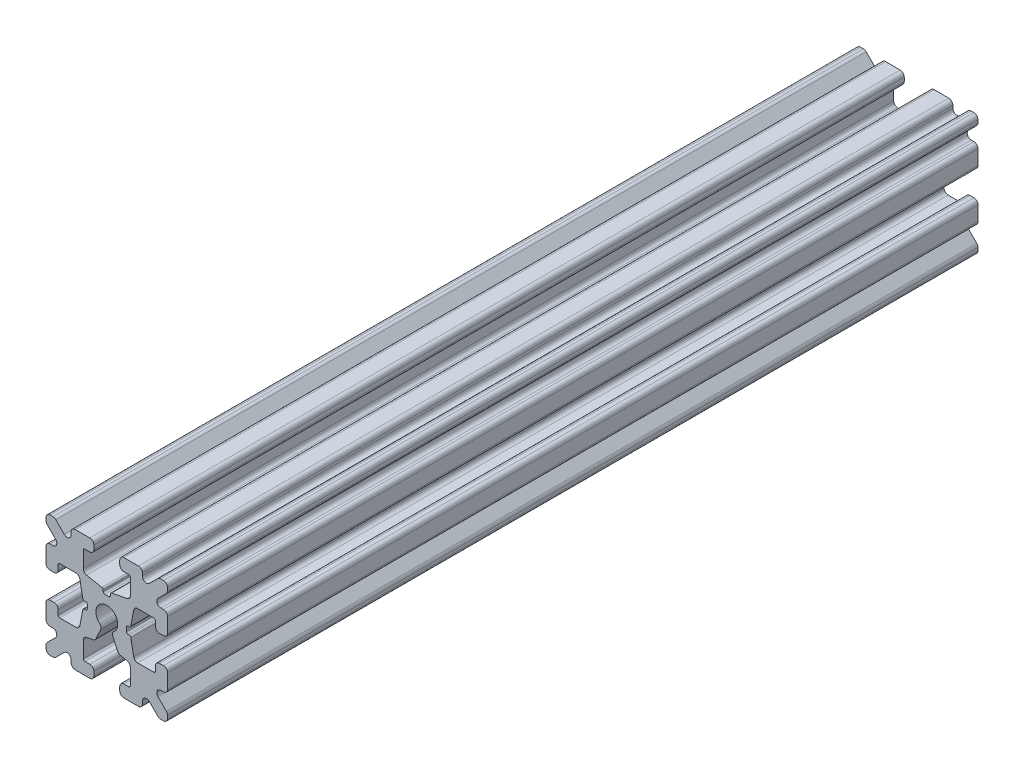
SolidWorks part; units mm, degrees
ref_plane "Front Plane" through (0, 0, 0) normal (0, 0, 1) x (1, 0, 0)
ref_plane "Top Plane" through (0, 0, 0) normal (0, 1, 0) x (1, 0, 0)
ref_plane "Right Plane" through (0, 0, 0) normal (1, 0, 0) x (0, 0, -1)
sketch "Sketch1" plane through (0, 0, 0) normal (0, 0, 1) x (1, 0, 0)
  line L1 (-7.5, -7.5) -> (7.5, -7.5)
  line L2 (-7.5, -7.5) -> (-7.5, 7.5)
  line L3 (-7.5, 7.5) -> (7.5, 7.5)
  line L4 (7.5, -7.5) -> (7.5, 7.5)
  line L5 (-7.5, -7.5) -> (7.5, 7.5) construction
  line L6 (-7.5, 7.5) -> (7.5, -7.5) construction
  circle A0 centre (0, 0) radius 1.35
  point P0 (0, 0)
  dimension "D2" = 2.7
  dimension "D1" = 15
extrude "Boss-Extrude1" add sketch "Sketch1" along normal mid plane 100
fillet "Fillet1" radius 0.5 4 edges at (7.5, -7.5, 0) (-7.5, -7.5, 0) (7.5, 7.5, 0) (-7.5, 7.5, 0)
sketch "Sketch2" plane through (0, 0, 50) normal (0, 0, 1) x (1, 0, 0)
  line L0 (-7.5, 7) -> (-7.5, -7) construction
  line L1 (-7.5, 1.6) -> (-6, 1.6)
  line L2 (-7.5, 1.6) -> (-7.5, -1.6)
  line L3 (-7.5, -1.6) -> (-6, -1.6)
  line L4 (-6, 1.6) -> (-6, 2.9)
  line L5 (0, 0) -> (-12.1036, 0) construction
  line L6 (-6, -2.9) -> (-3.4, -2.9)
  line L7 (0, 0) -> (-7, 7) construction
  line L8 (-6, 2.9) -> (-3.4, 2.9)
  line L9 (-3.4, -2.9) -> (-3.4, 2.9)
  line L10 (55, 0) -> (-55, 0) construction
  line L11 (-6, -2.9) -> (-6, -1.6)
  line L12 (2.9, 6) -> (1.6, 6)
  line L13 (2.9, 3.4) -> (-2.9, 3.4)
  line L14 (-2.9, 6) -> (-2.9, 3.4)
  line L15 (2.9, 6) -> (2.9, 3.4)
  line L16 (-1.6, 6) -> (-2.9, 6)
  line L17 (1.6, 7.5) -> (1.6, 6)
  line L18 (-1.6, 7.5) -> (1.6, 7.5)
  line L19 (-1.6, 7.5) -> (-1.6, 6)
  line L20 (-1.6, -7.5) -> (-1.6, -6)
  line L21 (-1.6, -7.5) -> (1.6, -7.5)
  line L22 (1.6, -7.5) -> (1.6, -6)
  line L23 (-1.6, -6) -> (-2.9, -6)
  line L24 (2.9, -6) -> (2.9, -3.4)
  line L25 (-2.9, -6) -> (-2.9, -3.4)
  line L26 (2.9, -3.4) -> (-2.9, -3.4)
  line L27 (2.9, -6) -> (1.6, -6)
  line L28 (6, -2.9) -> (6, -1.6)
  line L29 (3.4, -2.9) -> (3.4, 2.9)
  line L30 (6, 2.9) -> (3.4, 2.9)
  line L31 (6, -2.9) -> (3.4, -2.9)
  line L32 (6, 1.6) -> (6, 2.9)
  line L33 (7.5, -1.6) -> (6, -1.6)
  line L34 (7.5, 1.6) -> (7.5, -1.6)
  line L35 (7.5, 1.6) -> (6, 1.6)
  dimension "D1" = 3.2
  dimension "D2" = 5.8
  dimension "D3" = 1.5
  dimension "D4" = 2.6
extrude "Cut-Extrude1" cut sketch "Sketch2" against normal through all
sketch "Sketch4" plane through (0, 0, 50) normal (0, 0, 1) x (1, 0, 0)
  line L0 (-3.4, 2.9) -> (-2.85, 0)
  line L1 (55, 0) -> (-55, 0) construction
  line L2 (-2.85, 0) -> (-3.4, -2.9)
  line L3 (-3.4, -2.9) -> (-3.4, 2.9) construction
  line L4 (-3.4, 2.9) -> (-3.4, -2.9)
  line L5 (-2.9, 3.4) -> (0, 2.85)
  line L6 (0, 2.85) -> (2.9, 3.4)
  line L7 (2.9, 3.4) -> (-2.9, 3.4)
  line L8 (3.4, 2.9) -> (2.85, 0)
  line L9 (2.85, 0) -> (3.4, -2.9)
  line L10 (3.4, -2.9) -> (3.4, 2.9)
  line L11 (-2.9, -3.4) -> (0, -2.85)
  line L12 (0, -2.85) -> (2.9, -3.4)
  line L13 (2.9, -3.4) -> (-2.9, -3.4)
  circle A2 centre (0, 0) radius 2.85
  circle A3 centre (0, 0) radius 2.85 construction
  dimension "D1" = 1.5
extrude "Cut-Extrude3" cut sketch "Sketch4" against normal through all
fillet "Fillet3" radius 0.5 16 edges at (-6, -1.6, 0) (-7.5, -1.6, 0) (-6, 1.6, 0) (-7.5, 1.6, 0) (-1.6, -7.5, 0) (-1.6, -6, 0) (1.6, -7.5, 0) (1.6, -6, 0) (6, -1.6, 0) (7.5, -1.6, 0) (7.5, 1.6, 0) (6, 1.6, 0) (1.6, 7.5, 0) (1.6, 6, 0) (-1.6, 7.5, 0) (-1.6, 6, 0)
fillet "Fillet4" radius 0.5 8 edges at (-3.4, 2.9, 0) (-3.4, -2.9, 0) (2.9, -3.4, 0) (-2.9, -3.4, 0) (3.4, -2.9, 0) (3.4, 2.9, 0) (-2.9, 3.4, 0) (2.9, 3.4, 0)
fillet "Fillet5" radius 3 4 edges at (0, -2.85, 0) (2.85, 0, 0) (-2.85, 0, 0) (0, 2.85, 0)
fillet "Fillet6" radius 0.2 8 edges at (-2.9, -6, 0) (2.9, -6, 0) (6, -2.9, 0) (6, 2.9, 0) (2.9, 6, 0) (-2.9, 6, 0) (-6, -2.9, 0) (-6, 2.9, 0)
sketch "Sketch5" plane through (0, 0, 50) normal (0, 0, 1) x (1, 0, 0)
  line L0 (0, 0) -> (-7, 7) construction
  line L1 (-7.5, 6.4393) -> (-5.4607, 4.4)
  line L2 (-6.4393, 7.5) -> (-4.4, 5.4607)
  line L3 (-7.5, 4.4) -> (-5.4607, 4.4)
  line L4 (-3.8141, 2.9) -> (-5.8, 2.9) construction
  line L5 (0, 0) -> (-12.1819, 0) construction
  line L6 (-4.4, 7.5) -> (-4.4, 5.4607)
  line L7 (-2.9, 5.8) -> (-2.9, 3.8141) construction
  line L8 (-7.5, 6.4393) -> (-7.5, 4.4)
  line L9 (-7.5, 7) -> (-7.5, 2.1) construction
  line L10 (2.1, -7.5) -> (7, -7.5) construction
  line L11 (7.5, -7) -> (7.5, -2.1) construction
  line L12 (7, 7.5) -> (2.1, 7.5) construction
  line L13 (-2.1, 7.5) -> (-7, 7.5) construction
  line L14 (-4.4, 7.5) -> (-6.4393, 7.5)
  line L16 (55, 0) -> (-55, 0) construction
  line L17 (0, 0) -> (0, 10.993) construction
  line L18 (0, -54.6431) -> (0, 54.6431) construction
  line L20 (4.4, 7.5) -> (6.4393, 7.5)
  line L22 (7.5, 6.4393) -> (7.5, 4.4)
  line L23 (4.4, 7.5) -> (4.4, 5.4607)
  line L24 (7.5, 4.4) -> (5.4607, 4.4)
  line L25 (6.4393, 7.5) -> (4.4, 5.4607)
  line L26 (7.5, 6.4393) -> (5.4607, 4.4)
  line L27 (7.5, -6.4393) -> (5.4607, -4.4)
  line L28 (6.4393, -7.5) -> (4.4, -5.4607)
  line L29 (7.5, -4.4) -> (5.4607, -4.4)
  line L30 (4.4, -7.5) -> (4.4, -5.4607)
  line L31 (7.5, -6.4393) -> (7.5, -4.4)
  line L33 (4.4, -7.5) -> (6.4393, -7.5)
  line L36 (-4.4, -7.5) -> (-6.4393, -7.5)
  line L38 (-7.5, -6.4393) -> (-7.5, -4.4)
  line L39 (-4.4, -7.5) -> (-4.4, -5.4607)
  line L40 (-7.5, -4.4) -> (-5.4607, -4.4)
  line L41 (-6.4393, -7.5) -> (-4.4, -5.4607)
  line L42 (-7.5, -6.4393) -> (-5.4607, -4.4)
  dimension "D1" = 1.5
  dimension "D2" = 1.5
  dimension "D3" = 1.5
extrude "Cut-Extrude4" cut sketch "Sketch5" against normal through all
fillet "Fillet8" radius 0.5 24 edges at (-5.4607, 4.4, 0) (-7.5, 4.4, 0) (-5.4607, -4.4, 0) (-7.5, -4.4, 0) (-4.4, -7.5, 0) (-4.4, -5.4607, 0) (4.4, -7.5, 0) (4.4, -5.4607, 0) (5.4607, -4.4, 0) (7.5, -4.4, 0) (7.5, 4.4, 0) (5.4607, 4.4, 0) (4.4, 5.4607, 0) (4.4, 7.5, 0) (-4.4, 5.4607, 0) (-4.4, 7.5, 0) (-6.4393, 7.5, 0) (-7.5, 6.4393, 0) (6.4393, 7.5, 0) (7.5, 6.4393, 0) (6.4393, -7.5, 0) (7.5, -6.4393, 0) (-6.4393, -7.5, 0) (-7.5, -6.4393, 0)
sketch "Sketch6" plane through (0, 0, 50) normal (0, 0, 1) x (1, 0, 0)
  line L0 (0, 0) -> (0, 11.013) construction
  line L1 (0.559, 2.956) -> (2.1235, 2.956) construction
  line L2 (0, -54.6431) -> (0, 54.6431) construction
  line L3 (0, 0) -> (7, 7) construction
  line L4 (8.6552, 0.4445) -> (8.6552, -0.4445)
  line L5 (2.406, 0.4445) -> (8.6552, 0.4445)
  line L8 (2.406, -0.4445) -> (2.406, 0.4445)
  line L10 (8.6552, -0.4445) -> (2.406, -0.4445)
  line L11 (-8.6552, -0.4445) -> (-2.406, -0.4445)
  line L12 (-2.406, -0.4445) -> (-2.406, 0.4445)
  line L14 (-0.4445, 8.6552) -> (-0.4445, 2.406)
  line L15 (-0.4445, 2.406) -> (0.4445, 2.406)
  line L17 (0.4445, 2.406) -> (0.4445, 8.6552)
  line L18 (0.4445, 8.6552) -> (-0.4445, 8.6552)
  line L20 (-2.406, 0.4445) -> (-8.6552, 0.4445)
  line L21 (-8.6552, 0.4445) -> (-8.6552, -0.4445)
  point P7 (0, 2.5973)
  dimension "D3" = 0.55
  dimension "D1" = 0.889
extrude "Cut-Extrude5" cut sketch "Sketch6" against normal through all
sketch "Sketch7" plane through (0, 0, 50) normal (0, 0, 1) x (1, 0, 0)
  line L0 (0, 0) -> (-2.1533, -4.6178)
  line L1 (-2.1533, -4.6178) -> (2.1533, -4.6178)
  line L2 (2.1533, -4.6178) -> (0, 0)
  line L3 (0, 0) -> (0, -8.6832) construction
  line L4 (0, -54.6431) -> (0, 54.6431) construction
  dimension "D1" = 50
extrude "Cut-Extrude6" cut sketch "Sketch7" against normal through all
fillet "Fillet9" radius 0.5 4 edges at (0.5705, -1.2235, 0) (-0.5705, -1.2235, 0) (1.4579, -3.1265, 0) (-1.4579, -3.1265, 0)
fillet "Fillet10" radius 0.2 12 edges at (-2.406, 0.4445, 0) (-2.406, -0.4445, 0) (0.4445, 2.406, 0) (-0.4445, 2.406, 0) (2.406, 0.4445, 0) (2.406, -0.4445, 0) (-2.9366, -0.4445, 0) (-2.9366, 0.4445, 0) (2.9366, -0.4445, 0) (2.9366, 0.4445, 0) (0.4445, 2.9366, 0) (-0.4445, 2.9366, 0)
sketch "Sketch10" plane through (0, 0, 50) normal (0, 0, 1) x (1, 0, 0)
  line L0 (2.7, 6) -> (2.1, 6) construction
  line L1 (-2.75, 6) -> (2.75, 6)
  line L2 (-2.75, 6) -> (-2.75, 3.6)
  line L3 (-2.75, 3.6) -> (2.75, 3.6)
  line L4 (2.75, 6) -> (2.75, 3.6)
  line L5 (0, 0) -> (0, 8.8277) construction
  line L6 (-3.2398, 3.994) -> (-2.2083, 2.8606) construction
  line L7 (-3.878, 3.2131) -> (-3.2018, 2.4701) construction
  line L8 (-2.406, -0.2445) -> (-2.406, 0.2445) construction
  line L9 (-2.1, 7.5) -> (-3.9, 7.5) construction
  line L10 (-1.5, 7.5) -> (1.5, 7.5)
  line L11 (-1.5, 7.5) -> (-1.5, 3.5)
  line L12 (-1.5, 3.5) -> (1.5, 3.5)
  line L13 (1.5, 7.5) -> (1.5, 3.5)
  arc A1 (-3.3228, 2.4932) -> (-3.8141, 2.9) centre (-3.8141, 2.4) ccw construction
  arc A2 (-2.9, 3.8141) -> (-2.4932, 3.3228) centre (-2.4, 3.8141) ccw construction
  arc A3 (0.88, -1.0238) -> (-0.88, -1.0238) centre (0, 0) ccw construction
  point P19 (-1.35, 0)
  point P20 (-2.406, 0)
  dimension "D1" = 2.4
  dimension "D2" = 5.5
  dimension "D3" = 0.9976
  dimension "D4" = 3
  dimension "D5" = 4
sketch "Sketch11" plane through (0, 0, 50) normal (0, 0, 1) x (1, 0, 0)
  line L0 (-7.5, 7) -> (-7.5, 6.6464) construction
  line L1 (-7.5, 7.5) -> (7.5, 7.5) construction
  line L2 (-7.5, 7.5) -> (-7.5, -7.5) construction
  line L3 (-7.5, -7.5) -> (7.5, -7.5) construction
  line L4 (7.5, 7.5) -> (7.5, -7.5) construction
  line L5 (-7, -7.5) -> (-6.6464, -7.5) construction
  line L6 (7.5, 6.6464) -> (7.5, 7) construction
  line L7 (-2.1, 7.5) -> (-3.9, 7.5) construction
  point P0 (0, 7.5)
  point P1 (0, -7.5)
  point P2 (7.5, 0)
  point P3 (-7.5, 0)
sketch "Sketch12" plane through (0, 0, -50) normal (0, 0, -1) x (-1, 0, 0)
  line L1 (-7.5, -7.5) -> (7.5, -7.5) construction
  line L2 (-7.5, -7.5) -> (-7.5, 7.5) construction
  line L3 (-7.5, 7.5) -> (7.5, 7.5) construction
  line L4 (7.5, -7.5) -> (7.5, 7.5) construction
  point P4 (-7.5, 0)
  point P9 (0, -7.5)
  point P10 (7.5, 0)
  point P11 (0, 7.5)
sketch "Sketch13" plane through (0, -7.5, 0) normal (0, -1, 0) x (1, 0, 0)
  line L0 (0, 50) -> (0, -50) construction
  line L1 (-7.5, -50) -> (-7.5, 50) construction
  line L2 (7.5, 50) -> (7.5, -50) construction
sketch "Sketch14" plane through (-7.5, 0, 0) normal (-1, 0, 0) x (0, 0, 1)
  line L0 (50, 0) -> (-50, 0) construction
sketch "Sketch15" plane through (0, 7.5, 0) normal (0, 1, 0) x (1, 0, 0)
  line L0 (0, -50) -> (0, 50) construction
  line L1 (-7.5, -50) -> (7.5, -50) construction
  line L2 (-7.5, -50) -> (-7.5, 50) construction
  line L3 (7.5, 50) -> (7.5, -50) construction
sketch "Sketch16" plane through (7.5, 0, 0) normal (1, 0, 0) x (0, 0, -1)
  line L0 (-50, 0) -> (50, 0) construction
